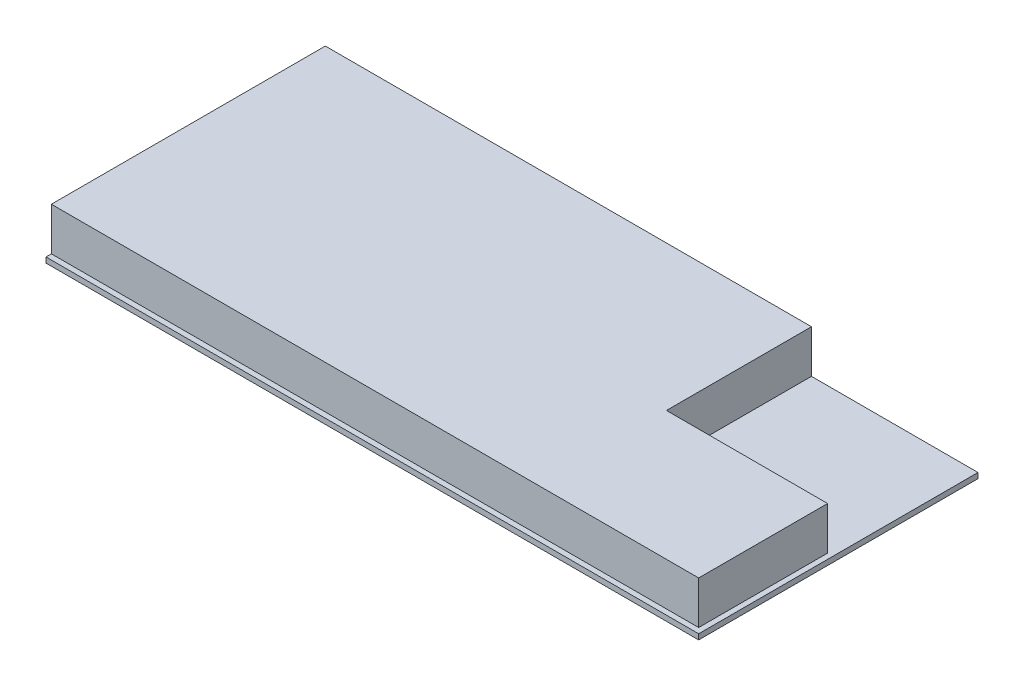
SolidWorks part; units mm, degrees
ref_plane "前视基准面" through (0, 0, 0) normal (0, 0, 1) x (1, 0, 0)
ref_plane "上视基准面" through (0, 0, 0) normal (0, 1, 0) x (1, 0, 0)
ref_plane "右视基准面" through (0, 0, 0) normal (1, 0, 0) x (0, 0, -1)
other "Configuration Table"
sketch "草图1" plane through (0, 0, 0) normal (0, 1, 0) x (1, 0, 0)
  line L1 (-6075, -1300) -> (0, -1300)
  line L2 (-6075, -1300) -> (-6075, 1300)
  line L3 (-6075, 1300) -> (0, 1300)
  line L4 (0, -1300) -> (0, 1300)
  line L5 (-6075, -1300) -> (0, 1300) construction
  line L6 (-6075, 1300) -> (0, -1300) construction
  point P0 (-3037.5, 0)
  dimension "D1" = 2600
  dimension "D2" = 6075
extrude "凸台-拉伸1" add sketch "草图1" along normal blind 50
sketch "草图2" plane through (0, 50, 0) normal (0, 1, 0) x (1, 0, 0)
  line L0 (0, 1300) -> (0, -1250)
  line L1 (0, 1300) -> (-6075, 1300) construction
  line L2 (0, -1250) -> (-6025, -1250)
  line L3 (-6025, -1250) -> (-6025, -50)
  line L4 (-6025, -50) -> (-4525, -50)
  line L5 (-4525, -50) -> (-4525, 1300)
  line L6 (-4525, 1300) -> (0, 1300)
  line L7 (-6075, 1300) -> (-6075, -1300) construction
  line L8 (-6075, -1300) -> (0, -1300) construction
  line L9 (0, -1300) -> (0, 1300) construction
  dimension "D1" = 1550
  dimension "D2" = 1350
  dimension "D3" = 50
  dimension "D4" = 50
extrude "凸台-拉伸2" add sketch "草图2" along normal blind 400
mirror "镜向1" about plane through (0, 50, 1300) normal (-1, 0, 0) of bodies 107
sketch "草图3" plane through (0, 450, 0) normal (0, 1, 0) x (1, 0, 0)
  line L0 (-6075, -1300) -> (6075, -1300) construction
  line L1 (-6075, 1300) -> (0, 1300)
  line L2 (-6075, 1300) -> (-6075, -1300)
  line L3 (-6075, -1300) -> (0, -1300)
  line L4 (0, 1300) -> (0, -1300)
extrude "切除-拉伸1" cut sketch "草图3" against normal through all
